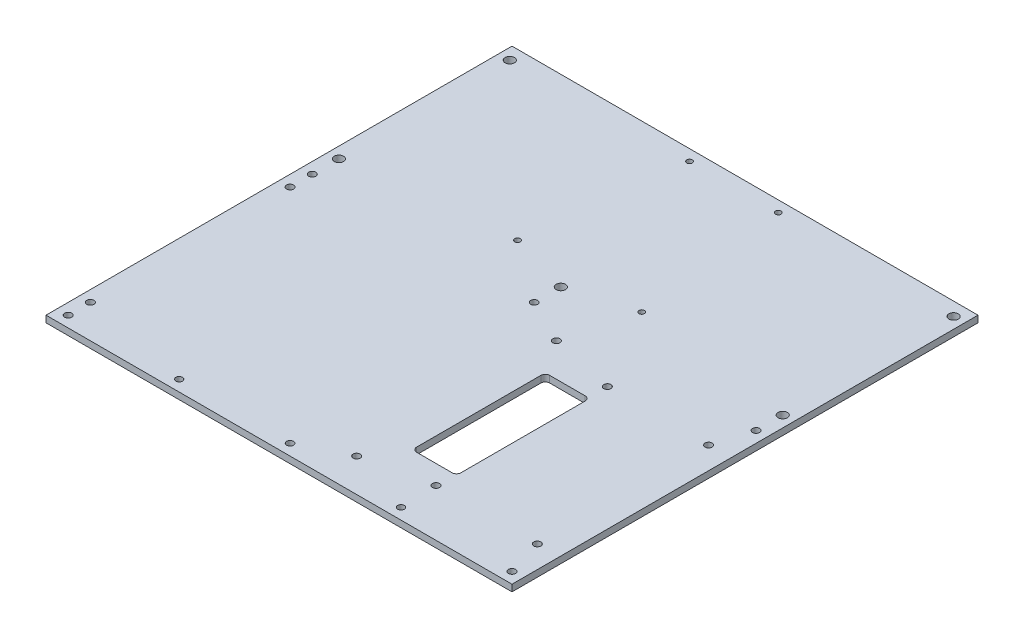
SolidWorks part; units mm, degrees
other "标注1"
sketch "草图5" plane through (-105, 2, -125) normal (0, 1, 0) x (1, 0, 0)
other "标注2"
sketch "草图6"
ref_plane "前视基准面" through (0, 0, 0) normal (0, 0, 1) x (1, 0, 0)
ref_plane "上视基准面" through (0, 0, 0) normal (0, 1, 0) x (1, 0, 0)
ref_plane "右视基准面" through (0, 0, 0) normal (1, 0, 0) x (0, 0, -1)
sketch "草图1" plane through (0, 0, 0) normal (0, 1, 0) x (1, 0, 0)
  line L1 (-105, -125) -> (105, -125)
  line L2 (-105, -125) -> (-105, 125)
  line L3 (-105, 125) -> (105, 125)
  line L4 (105, -125) -> (105, 125)
  line L5 (-105, -125) -> (105, 125) construction
  line L6 (-105, 125) -> (105, -125) construction
  point P0 (0, 0)
  dimension "D1" = 210
  dimension "D2" = 250
extrude "凸台-拉伸1" add sketch "草图1" along normal blind 3 contours L4 L3 L2 L1
sketch "草图2" plane through (0, 0, 0) normal (0, 1, 0) x (1, 0, 0)
  line L0 (105, -125) -> (105, 125) construction
  line L1 (-105, -125) -> (-105, 125) construction
  line L2 (105, 5) -> (-105, 5)
  line L3 (105, 5) -> (105, -125)
  line L4 (105, -125) -> (-105, -125)
  line L5 (-105, 5) -> (-105, -125)
  line L6 (105, 5) -> (-105, -125) construction
  line L7 (105, -125) -> (-105, 5) construction
  point P0 (0, -60)
  dimension "D1" = 130
  dimension "D2" = 5
extrude "切除-拉伸1" cut sketch "草图2" along normal through all
sketch "草图4" plane through (0, 3, 0) normal (0, 1, 0) x (1, 0, 0)
  line L0 (105, 5) -> (-105, 5) construction
  line L1 (30, 95) -> (50, 95)
  line L2 (30, 95) -> (30, 35)
  line L3 (30, 35) -> (50, 35)
  line L4 (50, 95) -> (50, 35)
  line L5 (30, 95) -> (50, 35) construction
  line L6 (30, 35) -> (50, 95) construction
  line L7 (-105, 5) -> (-105, 125) construction
  point P0 (40, 65)
  dimension "D1" = 20
  dimension "D2" = 60
  dimension "D3" = 30
  dimension "D4" = 135
extrude "切除-拉伸2" cut sketch "草图4" against normal through all both and the other way through all
fillet "圆角2" radius 2 4 edges at (50, 1.5, -35) (30, 1.5, -35) (50, 1.5, -95) (30, 1.5, -95)
sketch "草图7" plane through (0, 3, 0) normal (0, 1, 0) x (1, 0, 0)
  line L0 (126.6213, 65) -> (-117.7204, 65) construction
  line L1 (105, 5) -> (-105, 5) construction
  line L2 (-105, 125) -> (105, 125) construction
  line L3 (0, 0) -> (0, 165.5849) construction
  line L4 (105, 5) -> (105, 125) construction
  circle A0 centre (100, 120) radius 1.6
  circle A1 centre (0, 120) radius 1.55
  circle A2 centre (-100, 120) radius 1.6
  circle A3 centre (-100, 10) radius 1.6
  circle A4 centre (0, 10) radius 1.55
  circle A5 centre (100, 10) radius 1.6
  dimension "D1" = 3.2
  dimension "D2" = 3.1
  dimension "D3" = 5
  dimension "D4" = 5
extrude "切除-拉伸3" cut sketch "草图7" against normal through all both and the other way through all
sketch "草图8" plane through (0, 3, 0) normal (0, 1, 0) x (1, 0, 0)
  line L0 (0, 11.55) -> (0, 143.6329) construction
  line L1 (121.1596, 65) -> (-141.1928, 65) construction
  line L2 (105, 5) -> (-105, 5) construction
  line L3 (-105, 125) -> (105, 125) construction
  circle A0 centre (20, 20) radius 1.6
  circle A1 centre (-100, 20) radius 1.6
  circle A2 centre (-100, 110) radius 1.6
  circle A3 centre (20, 110) radius 1.6
  circle A4 centre (0, 10) radius 1.55 construction
  circle A5 centre (-50, 10) radius 1.5
  circle A6 centre (50, 10) radius 1.5
  circle A7 centre (95, 26.4) radius 1.6
  circle A8 centre (49.36, 26.4) radius 1.6
  circle A9 centre (49.36, 103.6) radius 1.6
  circle A10 centre (95, 103.6) radius 1.6
  dimension "D1" = 3.2
  dimension "D8" = 3
  dimension "D11" = 3.2
  dimension "D2" = 20
  dimension "D3" = 45
  dimension "D6" = 90
  dimension "D7" = 120
  dimension "D9" = 50
  dimension "D10" = 5
  dimension "D14" = 38.6
  dimension "D15" = 77.2
  dimension "D16" = 95
  dimension "D4" = 2
  dimension "D5" = 2
  dimension "D12" = 2
  dimension "D13" = 2
extrude "切除-拉伸4" cut sketch "草图8" against normal through all
sketch "草图9" plane through (0, 3, 0) normal (0, 1, 0) x (1, 0, 0)
  line L0 (-105, 125) -> (105, 125) construction
  line L1 (-105, 125) -> (105, 125)
  line L2 (-105, 125) -> (-105, 215)
  line L3 (-105, 215) -> (105, 215)
  line L4 (105, 125) -> (105, 215)
  dimension "D1" = 90
extrude "凸台-拉伸2" add sketch "草图9" against normal blind 3
sketch "草图10" plane through (0, 3, 0) normal (0, 1, 0) x (1, 0, 0)
  line L0 (0, 0) -> (0, 160.3211) construction
  circle A0 centre (100, 132) radius 2.1
  circle A1 centre (100, 120) radius 1.6 construction
  circle A2 centre (-100, 132) radius 2.1
  circle A3 centre (0, 132) radius 2.1
  dimension "D1" = 4.2
  dimension "D2" = 12
  dimension "D3" = 0
  dimension "D4" = 4.2
extrude "切除-拉伸5" cut sketch "草图10" against normal blind 10
sketch "草图11" plane through (0, 0, 0) normal (0, -1, 0) x (-1, 0, 0)
  line L0 (-20, 210) -> (20, 210) construction
  line L1 (0, 210) -> (0, -66.4399) construction
  line L2 (-28, 140.4586) -> (28, 140.4586) construction
  line L3 (-105, 215) -> (105, 215) construction
  circle A0 centre (20, 210) radius 1.25
  circle A3 centre (-20, 210) radius 1.25
  circle A4 centre (28, 140.4586) radius 1.25
  circle A6 centre (-28, 140.4586) radius 1.25
  circle A7 centre (20, 210) radius 70 construction
  point P5 (0, 140.4586)
  dimension "D1" = 2.5
  dimension "D3" = 56
  dimension "D4" = 2.5
  dimension "D5" = 140
  dimension "D6" = 5
  dimension "D7" = 2.5
  dimension "D8" = 2.5
  dimension "D2" = 40
extrude "切除-拉伸6" cut sketch "草图11" against normal through all
sketch "草图12" plane through (0, 3, 0) normal (0, 1, 0) x (1, 0, 0)
  line L0 (105, 215) -> (-105, 215) construction
  line L1 (0, 0) -> (0, 310.5154) construction
  line L3 (100, 132) -> (100, 172.0719) construction
  circle A0 centre (100, 209) radius 2.1
  circle A1 centre (-100, 209) radius 2.1
  dimension "D1" = 4.2
  dimension "D2" = 6
extrude "切除-拉伸7" cut sketch "草图12" against normal blind 10
